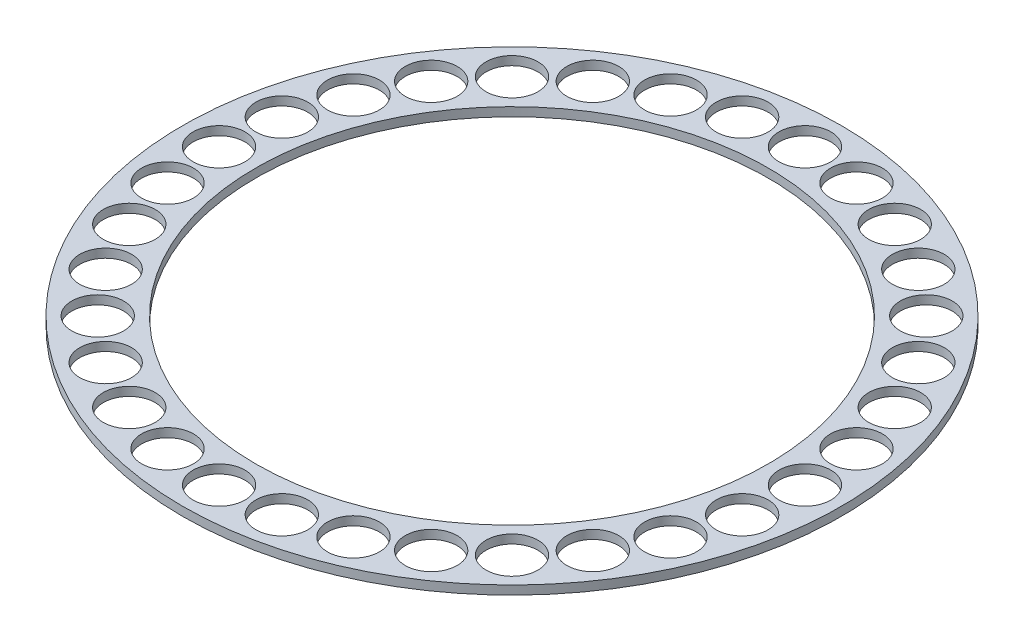
SolidWorks part; units mm, degrees
ref_plane "Front Plane" through (0, 0, 0) normal (0, 0, 1) x (1, 0, 0)
ref_plane "Top Plane" through (0, 0, 0) normal (0, 1, 0) x (1, 0, 0)
ref_plane "Right Plane" through (0, 0, 0) normal (1, 0, 0) x (0, 0, -1)
sketch "Sketch1" plane through (0, 0, 0) normal (0, 1, 0) x (1, 0, 0)
  circle A0 centre (0, 0) radius 142.875
  circle A4 centre (0, 0) radius 11.25
  point P6 (0, 0)
  dimension "D1" = 285.75
  dimension "D2" = 22.5
extrude "Boss-Extrude2" add sketch "Sketch1" against normal blind 3.81
sketch "Sketch2" plane through (0, 0, 0) normal (0, 1, 0) x (1, 0, 0)
  line L2 (-142.875, 0) -> (142.875, 0) construction
  circle A5 centre (0, 0) radius 142.875 construction
  circle A9 centre (-127, 0) radius 11.25
  circle A10 centre (0, 0) radius 115.75 construction
  dimension "D1" = 22.5
  dimension "D2" = 127
  dimension "D3" = 231.5
extrude "Cut-Extrude1" cut sketch "Sketch2" against normal through all
sketch "Sketch4" plane through (0, 0, 0) normal (0, 1, 0) x (1, 0, 0)
  line L8 (-13.3205, 10.795) -> (-10.795, 10.795)
  line L9 (-10.795, 10.795) -> (-10.795, 16.3468)
  line L10 (10.795, 13.385) -> (10.795, 10.795)
  line L23 (10.795, 10.795) -> (14.5573, 10.795)
  line L24 (-15.5509, -10.795) -> (-10.795, -10.795)
  line L25 (10.795, -14.2763) -> (10.795, -10.795)
  line L27 (10.795, -10.795) -> (14.3306, -10.795)
  line L28 (-10.795, -14.0687) -> (-10.795, -10.795)
  circle A0 centre (0, 0) radius 111.125
  circle A2 centre (0, 0) radius 11.25 construction
  point P4 (0, 50.5441)
  point P25 (0, 0)
  dimension "D1" = 222.25
  dimension "D5" = 10.795
  dimension "D3" = 10.795
  dimension "D6" = 10.795
  dimension "D7" = 10.795
  dimension "D9" = 10.795
  dimension "D12" = 10.795
  dimension "D13" = 10.795
  dimension "D14" = 10.795
extrude "Cut-Extrude2" cut sketch "Sketch4" against normal through all and the other way through all
pattern_circular "CirPattern1" count 32 over 360 about axis through (0, 0, 0) along (0, 1, 0) of "Cut-Extrude1"
